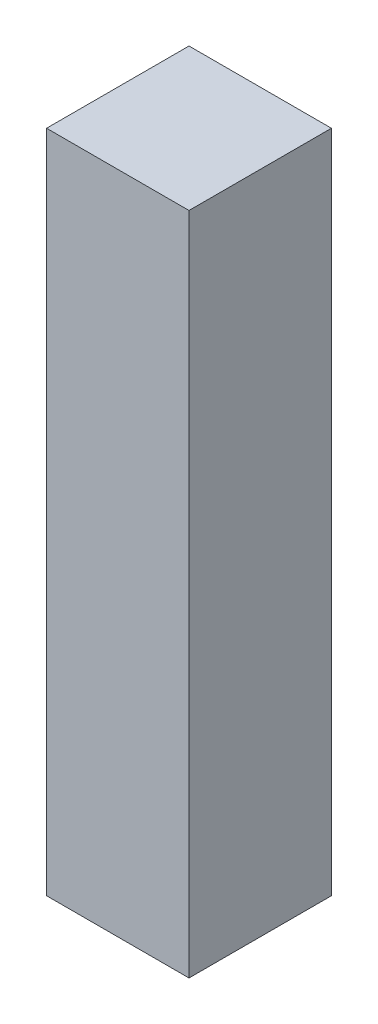
SolidWorks part; units mm, degrees
ref_plane "Front Plane" through (0, 0, 0) normal (0, 0, 1) x (1, 0, 0)
ref_plane "Top Plane" through (0, 0, 0) normal (0, 1, 0) x (1, 0, 0)
ref_plane "Right Plane" through (0, 0, 0) normal (1, 0, 0) x (0, 0, -1)
sketch "Sketch1" plane through (0, 0, 0) normal (0, 1, 0) x (1, 0, 0)
  line L1 (0, 0) -> (15, 0)
  line L2 (0, 0) -> (0, 15)
  line L3 (0, 15) -> (15, 15)
  line L4 (15, 0) -> (15, 15)
  dimension "D1" = 15
extrude "Boss-Extrude1" add sketch "Sketch1" along normal blind 70
